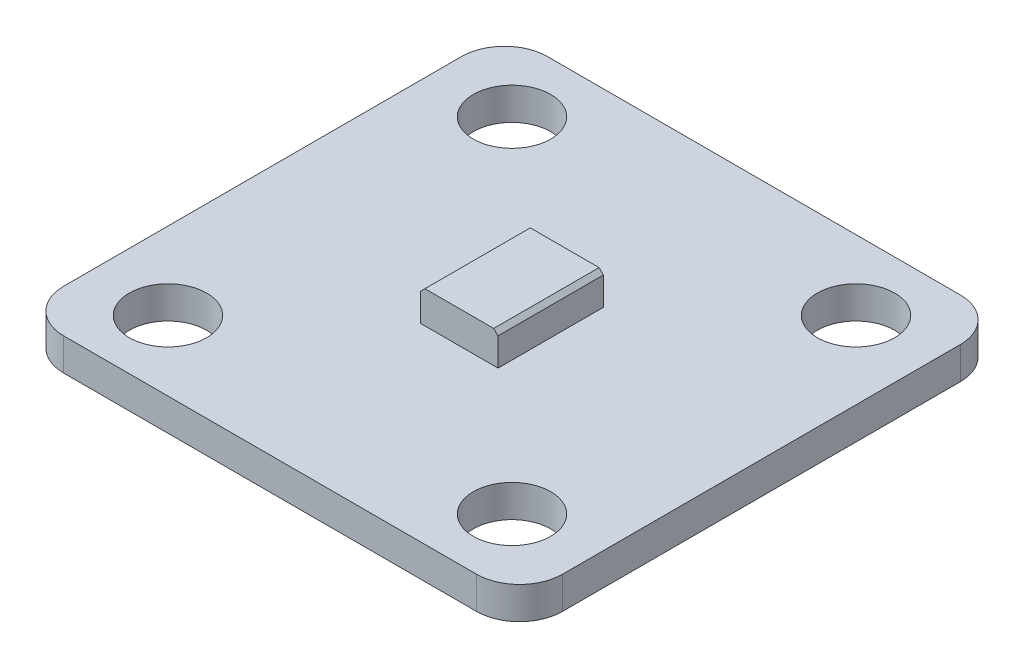
SolidWorks part; units mm, degrees
ref_plane "前视基准面" through (0, 0, 0) normal (0, 0, 1) x (1, 0, 0)
ref_plane "上视基准面" through (0, 0, 0) normal (0, 1, 0) x (1, 0, 0)
ref_plane "右视基准面" through (0, 0, 0) normal (1, 0, 0) x (0, 0, -1)
sketch "草图1" plane through (0, 0, 0) normal (0, 1, 0) x (1, 0, 0)
  line L1 (-11.6, 11.25) -> (11.6, 11.25)
  line L2 (-11.6, 11.25) -> (-11.6, -11.25)
  line L3 (-11.6, -11.25) -> (11.6, -11.25)
  line L4 (11.6, 11.25) -> (11.6, -11.25)
  line L5 (-11.6, 11.25) -> (11.6, -11.25) construction
  line L6 (-11.6, -11.25) -> (11.6, 11.25) construction
  point P0 (0, 0)
  dimension "D1" = 23.2
  dimension "D2" = 22.5
extrude "凸台-拉伸1" add sketch "草图1" along normal blind 1.5
fillet "圆角1" radius 2 4 edges at (-11.6, 0.75, -11.25) (11.6, 0.75, -11.25) (-11.6, 0.75, 11.25) (11.6, 0.75, 11.25)
sketch "草图2" plane through (0, 0, 0) normal (0, -1, 0) x (1, 0, 0)
  line L1 (-8, 8) -> (8, 8)
  line L2 (-8, 8) -> (-8, -8)
  line L3 (-8, -8) -> (8, -8)
  line L4 (8, 8) -> (8, -8)
  line L5 (-8, 8) -> (8, -8) construction
  line L6 (-8, -8) -> (8, 8) construction
  circle A0 centre (-8, 8) radius 1.8
  circle A1 centre (8, 8) radius 1.8
  circle A2 centre (8, -8) radius 1.8
  circle A3 centre (-8, -8) radius 1.8
  point P0 (0, 0)
  point P16 (0, 0)
  dimension "D3" = 3.6
  dimension "D1" = 16
  dimension "D2" = 16
  dimension "D4" = 4
extrude "切除-拉伸1" cut sketch "草图2" against normal blind 1.5 contours A0 | A1 | A3 | A2
sketch "草图3" plane through (0, 1.5, 0) normal (0, 1, 0) x (1, 0, 0)
  line L1 (-1.8, 2.45) -> (1.8, 2.45)
  line L2 (-1.8, 2.45) -> (-1.8, -2.45)
  line L3 (-1.8, -2.45) -> (1.8, -2.45)
  line L4 (1.8, 2.45) -> (1.8, -2.45)
  line L5 (-1.8, 2.45) -> (1.8, -2.45) construction
  line L6 (-1.8, -2.45) -> (1.8, 2.45) construction
  point P0 (0, 0)
  dimension "D1" = 3.6
  dimension "D2" = 4.9
extrude "凸台-拉伸2" add sketch "草图3" along normal blind 1.5
chamfer "倒角1" distance 0.2 angle 45 2 edges at (1.8, 3, 0) (-1.8, 3, 0)
sketch "草图4" plane through (0, 1.5, 0) normal (0, 1, 0) x (1, 0, 0)
  line L0 (-1.8, -2.45) -> (-1.8, -2.2963)
  line L1 (-1.8, 2.45) -> (-1.8, -2.45) construction
  line L2 (-1.8, -2.2963) -> (-2.6501, -2.2963)
  line L3 (-2.6501, -2.2963) -> (-2.6501, -1.7963)
  line L4 (-2.6501, -1.7963) -> (-2.3501, -1.7963)
  line L5 (-2.3501, -1.7963) -> (-2.3501, -2.2963)
  point P9 (0, 0)
  dimension "D1" = 0.3
  dimension "D2" = 0.5
sketch "草图5" plane through (0, 0, 2.45) normal (0, 0, 1) x (1, 0, 0)
  line L0 (-1.8, 1.5) -> (-2.6501, 1.5) construction
  line L1 (-1.8, 2.8) -> (-1.8, 1.5) construction
  spline S0 degree 3 poles (-2.3429, 1.5) (-1.9057, 1.7891) (-2.3618, 2.539) (-1.8, 2.687) knots 0 0 0 0 1 1 1 1
  point P2 (-2.1245, 2.0037)
sketch "草图17" plane through (0, 0, 0) normal (0, -1, 0) x (1, 0, 0)
  circle A0 centre (0, 0) radius 0.5
  dimension "D1" = 1
extrude "切除-拉伸2" cut sketch "草图17" against normal blind 0.1
